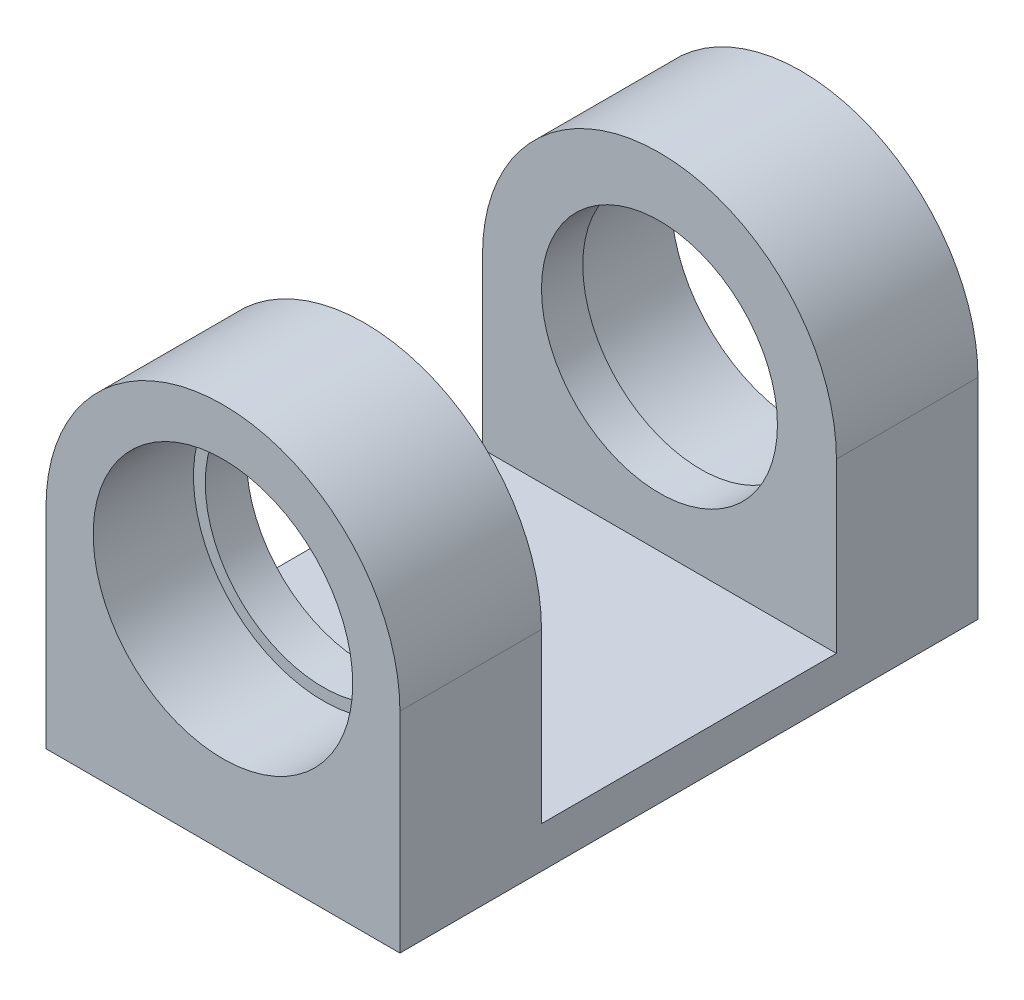
SolidWorks part; units mm, degrees
ref_plane "Alzado" through (0, 0, 0) normal (0, 0, 1) x (1, 0, 0)
ref_plane "Planta" through (0, 0, 0) normal (0, 1, 0) x (1, 0, 0)
ref_plane "Vista lateral" through (0, 0, 0) normal (1, 0, 0) x (0, 0, -1)
sketch "Croquis2" plane through (0, 0, 0) normal (0, 0, 1) x (1, 0, 0)
  line L1 (0, 0) -> (-30, 0)
  line L2 (0, 0) -> (0, 17.76)
  line L4 (-30, 0) -> (-30, 17.76)
  arc A0 (0, 17.76) -> (-30, 17.76) centre (-15, 17.76) ccw
  dimension "D1" = 30
  dimension "D2" = 17.76
extrude "Saliente-Extruir1" add sketch "Croquis2" along normal mid plane 12
sketch "Croquis3" plane through (0, 0, 6) normal (0, 0, 1) x (1, 0, 0)
  circle A0 centre (-15, 17.76) radius 4
  dimension "D1" = 8
extrude "Cortar-Extruir1" cut sketch "Croquis3" against normal through all
ref_plane "Plano1" through (-15, 0, 0) normal (-1, 0, 0) x (0, 0, 1)
sketch "Croquis4" plane through (0, 0, 6) normal (0, 0, 1) x (1, 0, 0)
  circle A0 centre (-15, 17.76) radius 11
  dimension "D1" = 22
extrude "Cortar-Extruir2" cut sketch "Croquis4" against normal blind 8.5
sketch "Croquis5" plane through (0, 0, -2.5) normal (0, 0, 1) x (1, 0, 0)
  circle A0 centre (-15, 17.76) radius 10
  dimension "D1" = 20
extrude "Cortar-Extruir3" cut sketch "Croquis5" against normal blind 8.5
sketch "Croquis6" plane through (0, 0, -6) normal (0, 0, -1) x (-1, 0, 0)
  line L0 (30, 17.76) -> (30, 0) construction
  line L1 (0, 0) -> (30, 0)
  line L2 (0, 0) -> (0, 3.5)
  line L3 (0, 3.5) -> (30, 3.5)
  line L4 (30, 0) -> (30, 3.5)
  dimension "D1" = 3.5
extrude "Saliente-Extruir2" add sketch "Croquis6" along normal blind 25
ref_plane "Plano2" through (0, 0, -18.5) normal (0, 0, -1) x (-1, 0, 0)
mirror "Simetría1" about plane through (0, 0, -18.5) normal (0, 0, -1) of "Cortar-Extruir3", "Cortar-Extruir2", "Saliente-Extruir1"
